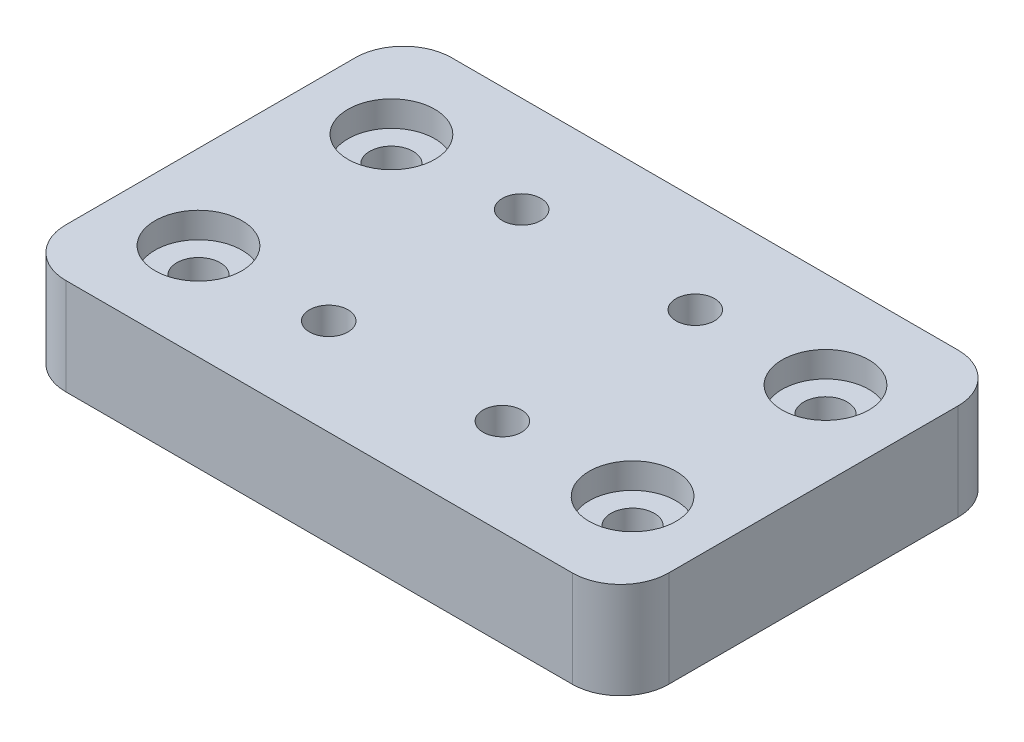
SolidWorks part; units mm, degrees
ref_plane "Płaszczyzna przednia" through (0, 0, 0) normal (0, 0, 1) x (1, 0, 0)
ref_plane "Płaszczyzna górna" through (0, 0, 0) normal (0, 1, 0) x (1, 0, 0)
ref_plane "Płaszczyzna prawa" through (0, 0, 0) normal (1, 0, 0) x (0, 0, -1)
sketch "Szkic1" plane through (0, 0, 0) normal (0, 1, 0) x (1, 0, 0)
  line L1 (-52.5, -40) -> (52.5, -40)
  line L2 (-62.5, -30) -> (-62.5, 30)
  line L3 (-52.5, 40) -> (52.5, 40)
  line L4 (62.5, -30) -> (62.5, 30)
  line L5 (-62.5, -40) -> (62.5, 40) construction
  line L6 (-62.5, 40) -> (62.5, -40) construction
  arc A0 (-52.5, -40) -> (-62.5, -30) centre (-52.5, -30) cw
  arc A1 (52.5, -40) -> (62.5, -30) centre (52.5, -30) ccw
  arc A2 (52.5, 40) -> (62.5, 30) centre (52.5, 30) cw
  arc A3 (-62.5, 30) -> (-52.5, 40) centre (-52.5, 30) cw
  point P0 (0, 0)
  dimension "D3" = 10
  dimension "D1" = 125
  dimension "D2" = 80
extrude "Dodanie-wyciągnięcie1" add sketch "Szkic1" along normal blind 20
sketch "Szkic2" plane through (0, 20, 0) normal (0, 1, 0) x (1, 0, 0)
  line L0 (0, 54.8164) -> (0, -66.2219) construction
  line L1 (-103.5809, 0) -> (124.7626, 0) construction
  circle A0 centre (-18, 20) radius 4
  circle A1 centre (-18, -20) radius 4
  circle A2 centre (18, -20) radius 4
  circle A3 centre (18, 20) radius 4
  circle A4 centre (-45, 20) radius 4
  circle A5 centre (-45, -20) radius 4
  circle A6 centre (45, -20) radius 4
  circle A7 centre (45, 20) radius 4
  dimension "D1" = 8
  dimension "D4" = 8
  dimension "D6" = 90
  dimension "D2" = 40
  dimension "D3" = 36
  dimension "D5" = 40
hole_wizard "Otwory ustalające Ø8.0mm1" positions "Szkic3" profile "Szkic4" hole size "Ø8.0" standard "ISO"
sketch "Szkic3" plane through (0, 20, 0) normal (0, 1, 0) x (1, 0, 0)
  point P0 (-18, -20)
  point P3 (18, -20)
  point P6 (18, 20)
  point P9 (-18, 20)
sketch "Szkic4" plane through (-18, 20, 20) normal (1, 0, 0) x (0, 0, 1)
  line L0 (0, 0) -> (0, 17.4034)
  line L1 (0, 17.4034) -> (4, 15)
  line L2 (4, 15) -> (4, 0)
  line L5 (4, 0) -> (0, 0)
  line L10 (0, 17.4034) -> (-4, 15) construction
  line L11 (0, -6.35) -> (0, 107.95) construction
  dimension "Średnica otworu" = 8
  dimension "Głębokość otworu" = 15
  dimension "Kąt wiertła" = 118
hole_wizard "Pogłębienie walcowe pod M8 śrubę z łbem szeciokątnym1" positions "Szkic5" profile "Szkic6" counterbore size "M8" standard "ISO" end condition through all
sketch "Szkic5" plane through (0, 20, 0) normal (0, 1, 0) x (1, 0, 0)
  point P0 (-45, 20)
  point P3 (-45, -20)
  point P6 (45, -20)
  point P9 (45, 20)
sketch "Szkic6" plane through (-45, 20, -20) normal (1, 0, 0) x (0, 0, 1)
  line L0 (0, 0) -> (0, 20)
  line L1 (0, 20) -> (4.5, 20)
  line L3 (4.5, 20) -> (4.5, 5.3)
  line L4 (4.5, 5.3) -> (9.0055, 5.3)
  line L5 (9.0055, 5.3) -> (9.0055, 0)
  line L7 (9.0055, 0) -> (0, 0)
  line L11 (0, -6.35) -> (0, 107.95) construction
  dimension "Średnica otworu na wylot" = 9
  dimension "Głębokość otworu na wylot" = 20
  dimension "Średnica pogłębienia walcowego" = 18.011
  dimension "Głębokość pogłębienia walcowego" = 5.3
